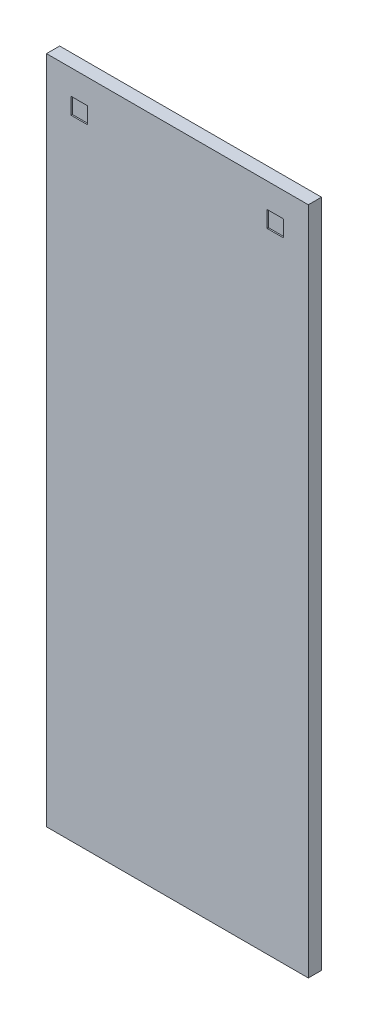
SolidWorks part; units mm, degrees
ref_plane "Front Plane" through (0, 0, 0) normal (0, 0, 1) x (1, 0, 0)
ref_plane "Top Plane" through (0, 0, 0) normal (0, 1, 0) x (1, 0, 0)
ref_plane "Right Plane" through (0, 0, 0) normal (1, 0, 0) x (0, 0, -1)
sketch "Sketch1" plane through (0, 0, 0) normal (0, 0, 1) x (1, 0, 0)
  line L1 (199, -509) -> (-199, -509)
  line L2 (199, -509) -> (199, 509)
  line L3 (199, 509) -> (-199, 509)
  line L4 (-199, -509) -> (-199, 509)
  line L5 (199, -509) -> (-199, 509) construction
  line L6 (199, 509) -> (-199, -509) construction
  point P0 (0, 0)
  dimension "D1" = 1018
  dimension "D2" = 398
extrude "Boss-Extrude1" add sketch "Sketch1" along normal blind 20 contours L4 L3 L2 L1
sketch "Sketch2" plane through (0, 0, 20) normal (0, 0, 1) x (1, 0, 0)
  line L0 (-199, 459) -> (199, 459) construction
  line L1 (-199, -509) -> (-199, 509) construction
  line L2 (199, -509) -> (199, 509) construction
  line L3 (199, 509) -> (-199, 509) construction
  line L4 (-149, 509) -> (-149, -509) construction
  line L5 (199, -509) -> (-199, -509) construction
  line L6 (-149, 459) -> (149, 459) construction
  line L8 (161.5, 446.5) -> (136.5, 446.5)
  line L9 (161.5, 446.5) -> (161.5, 471.5)
  line L10 (161.5, 471.5) -> (136.5, 471.5)
  line L11 (136.5, 446.5) -> (136.5, 471.5)
  line L12 (161.5, 446.5) -> (136.5, 471.5) construction
  line L13 (161.5, 471.5) -> (136.5, 446.5) construction
  line L14 (-136.5, 446.5) -> (-161.5, 446.5)
  line L15 (-136.5, 446.5) -> (-136.5, 471.5)
  line L16 (-136.5, 471.5) -> (-161.5, 471.5)
  line L17 (-161.5, 446.5) -> (-161.5, 471.5)
  line L18 (-136.5, 446.5) -> (-161.5, 471.5) construction
  line L19 (-136.5, 471.5) -> (-161.5, 446.5) construction
  dimension "D3" = 25
  dimension "D5" = 25
  dimension "D1" = 50
  dimension "D2" = 50
  dimension "D4" = 298
  dimension "D6" = 25
  dimension "D7" = 25
sketch "Sketch4" plane through (0, 0, 20) normal (0, 0, 1) x (1, 0, 0)
  line L0 (-306.4993, 633.6961) -> (-306.4993, -708.231) construction
extrude "Cut-Extrude1" cut sketch "Sketch2" against normal blind 2
